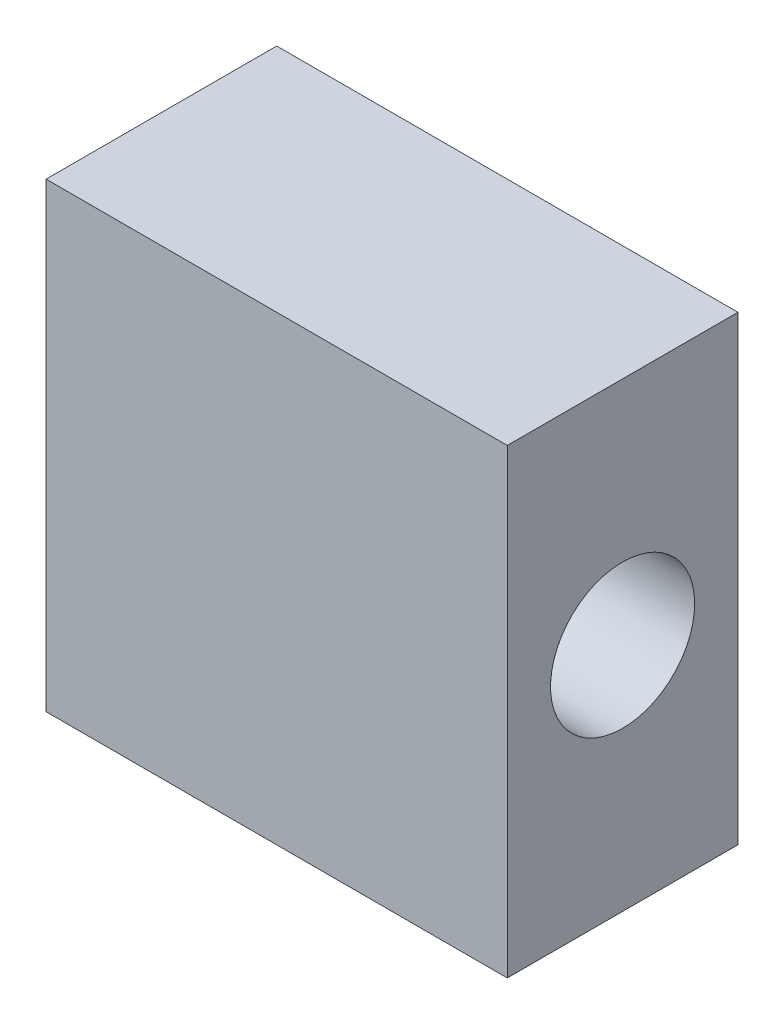
SolidWorks part; units mm, degrees
material "Brass"
ref_plane "Front Plane" through (0, 0, 0) normal (0, 0, 1) x (1, 0, 0)
ref_plane "Top Plane" through (0, 0, 0) normal (0, 1, 0) x (1, 0, 0)
ref_plane "Right Plane" through (0, 0, 0) normal (1, 0, 0) x (0, 0, -1)
sketch "Sketch1" plane through (0, 0, 0) normal (0, 0, 1) x (1, 0, 0)
  line L0 (0, 0) -> (50.8, 50.8) construction
  line L1 (0, 0) -> (50.8, 0)
  line L2 (0, 0) -> (0, 50.8)
  line L3 (0, 50.8) -> (50.8, 50.8)
  line L4 (50.8, 0) -> (50.8, 50.8)
  circle A0 centre (9.6846, 9.6846) radius 6.35 construction
  circle A1 centre (41.1154, 41.1154) radius 6.35 construction
  circle A2 centre (25.4, 25.4) radius 22.225 construction
  dimension "D2" = 44.45
  dimension "D3" = 12.7
  dimension "D1" = 50.8
extrude "Boss-Extrude1" add sketch "Sketch1" along normal blind 25.4
sketch "Sketch2" plane through (50.8, 0, 0) normal (1, 0, 0) x (0, 0, -1)
  line L0 (-25.4, 50.8) -> (0, 0) construction
  circle A0 centre (-12.7, 25.4) radius 7.9375
  dimension "D1" = 15.875
extrude "Cut-Extrude1" cut sketch "Sketch2" against normal blind 25.4
sketch "Sketch3" plane through (0, 0, 25.4) normal (0, 0, 1) x (1, 0, 0)
  line L0 (50.8, 25.4) -> (-18.0945, 25.4)
  line L1 (50.8, 0) -> (50.8, 50.8) construction
  line L2 (-18.0945, 25.4) -> (-18.0945, 47.186)
ref_plane "Plane1" through (0, 0, 0) normal (-0.8145, 0, -0.5802) x (-0.5802, 0, 0.8145)
ref_plane "Plane2" through (0.0279, -0.5327, 1.0653) normal (0.0235, -0.4471, 0.8942) x (0.9997, 0.0105, -0.021)
